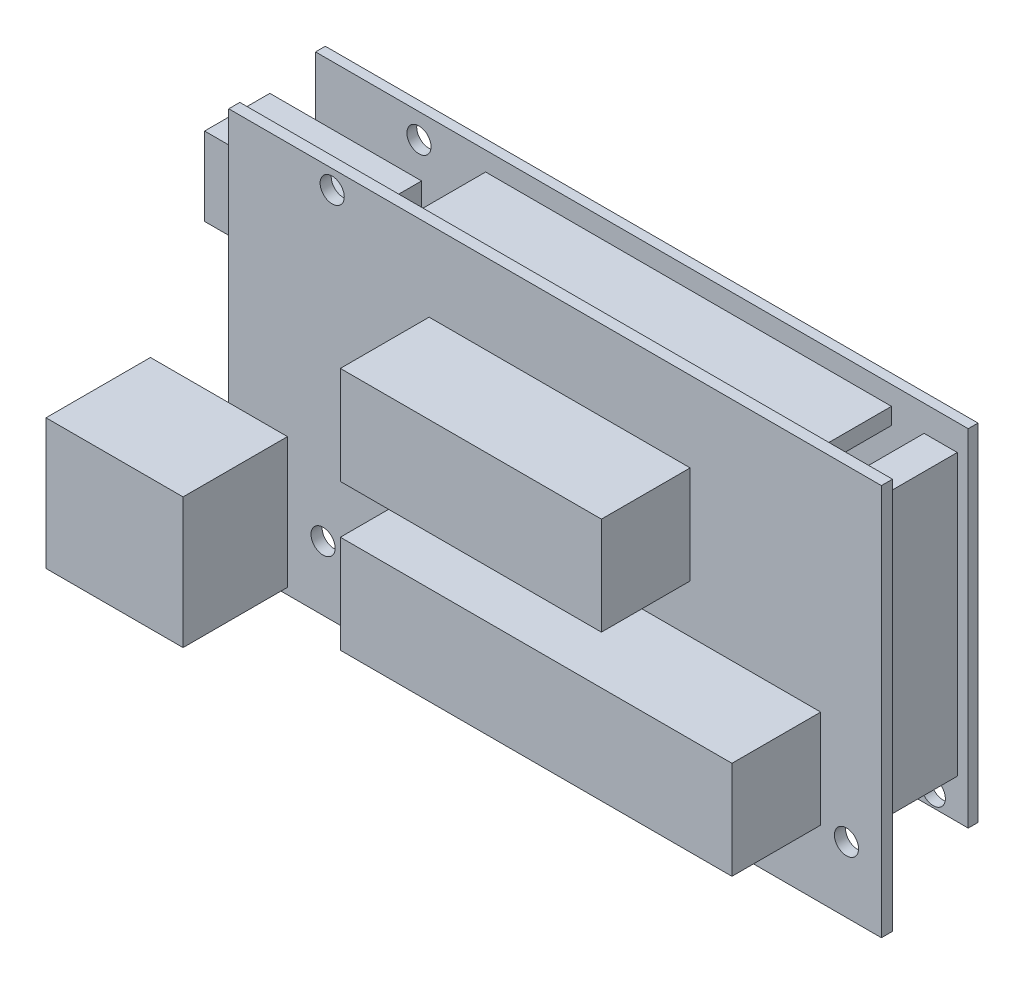
SolidWorks part; units mm, degrees
ref_plane "Plano frontal" through (0, 0, 0) normal (0, 0, 1) x (1, 0, 0)
ref_plane "Plano superior" through (0, 0, 0) normal (0, 1, 0) x (1, 0, 0)
ref_plane "Plano direito" through (0, 0, 0) normal (1, 0, 0) x (0, 0, -1)
sketch "Esboço1" plane through (0, 0, 0) normal (0, 0, 1) x (1, 0, 0)
  line L1 (-50, 30) -> (50, 30)
  line L2 (-50, 30) -> (-50, -30)
  line L3 (-50, -30) -> (50, -30)
  line L4 (50, 30) -> (50, -30)
  line L5 (-50, 30) -> (50, -30) construction
  line L6 (-50, -30) -> (50, 30) construction
  circle A0 centre (-34.15, 27.15) radius 1.85
  circle A1 centre (-35.55, -20.15) radius 1.85
  circle A2 centre (44.65, -19.95) radius 1.85
  point P0 (0, 0)
  dimension "D3" = 1
  dimension "D4" = 3.7
  dimension "D5" = 14
  dimension "D6" = 12.6
  dimension "D7" = 8
  dimension "D8" = 3.5
  dimension "D9" = 8.2
  dimension "D1" = 60
  dimension "D2" = 100
extrude "Ressalto-extrusão1" add sketch "Esboço1" along normal blind 1.7
sketch "Esboço2" plane through (0, 0, 1.7) normal (0, 0, 1) x (1, 0, 0)
  line L0 (-50, -30) -> (50, -30) construction
  line L1 (-19.3, -4.7) -> (40.7, -4.7)
  line L2 (-19.3, -4.7) -> (-19.3, -19.7)
  line L3 (-19.3, -19.7) -> (40.7, -19.7)
  line L4 (40.7, -4.7) -> (40.7, -19.7)
  line L5 (50, -30) -> (50, 30) construction
  line L7 (-19.3, 2.7) -> (20.7, 2.7)
  line L8 (-19.3, 2.7) -> (-19.3, 17.7)
  line L9 (-19.3, 17.7) -> (20.7, 17.7)
  line L10 (20.7, 2.7) -> (20.7, 17.7)
  dimension "D1" = 60
  dimension "D2" = 15
  dimension "D3" = 10.3
  dimension "D4" = 9.3
  dimension "D5" = 40
  dimension "D6" = 7.4
extrude "Ressalto-extrusão2" add sketch "Esboço2" along normal blind 13.6
sketch "Esboço3" plane through (0, 0, 0) normal (0, 0, -1) x (-1, 0, 0)
  line L0 (50, -30) -> (-50, -30) construction
  line L1 (50, 30.9) -> (-50, 30.9)
  line L2 (50, 30.9) -> (50, -22.1)
  line L3 (50, -22.1) -> (-50, -22.1)
  line L4 (-50, 30.9) -> (-50, -22.1)
  line L5 (50, 30) -> (50, -30) construction
  line L6 (-50, -30) -> (-50, 30) construction
  circle A0 centre (-44.65, -19.95) radius 1.85 construction
  circle A1 centre (34.15, 27.15) radius 1.85 construction
  circle A2 centre (35.55, -20.15) radius 1.85 construction
  circle A3 centre (-44.65, -19.95) radius 1.85
  circle A4 centre (34.15, 27.15) radius 1.85
  circle A5 centre (35.55, -20.15) radius 1.85
  dimension "D1" = 7.9
  dimension "D2" = 53
extrude "Ressalto-extrusão6" add sketch "Esboço3" along normal blind 1.5 from offset 11.6 separate body
sketch "Esboço4" plane through (0, 0, -11.6) normal (0, 0, 1) x (1, 0, 0)
  line L1 (-23.9415, 27.9898) -> (38.2426, 27.9898)
  line L2 (-23.9415, 27.9898) -> (-23.9415, 25.4498)
  line L3 (-23.9415, 25.4498) -> (38.2426, 25.4498)
  line L4 (38.2426, 27.9898) -> (38.2426, 25.4498)
  line L5 (48.3249, 26.9052) -> (43.2449, 26.9052)
  line L6 (48.3249, 26.9052) -> (48.3249, -16.0526)
  line L7 (48.3249, -16.0526) -> (43.2449, -16.0526)
  line L8 (43.2449, 26.9052) -> (43.2449, -16.0526)
  line L9 (38.2426, -19.9599) -> (-17.8292, -19.9599)
  line L10 (38.2426, -19.9599) -> (38.2426, -17.4199)
  line L11 (38.2426, -17.4199) -> (-17.8292, -17.4199)
  line L12 (-17.8292, -19.9599) -> (-17.8292, -17.4199)
  dimension "D1" = 2.54
  dimension "D2" = 5.08
extrude "Ressalto-extrusão8" add sketch "Esboço4" along normal up to surface (11.6 mm away) up to face at (0, 0, 0)
sketch "Esboço6" plane through (0, 0, 1.7) normal (0, 0, 1) x (1, 0, 0)
  line L0 (-50, -30) -> (50, -30) construction
  line L1 (-62, -9) -> (-41, -9)
  line L2 (-62, -9) -> (-62, -29)
  line L3 (-62, -29) -> (-41, -29)
  line L4 (-41, -9) -> (-41, -29)
  line L5 (-50, 30) -> (-50, -30) construction
  point P4 (-36.931, -25.6688)
  point P5 (-60.8994, -24.8784)
  dimension "D1" = 20
  dimension "D2" = 1
  dimension "D3" = 12
  dimension "D4" = 21
extrude "Ressalto-extrusão9" add sketch "Esboço6" along normal blind 16
sketch "Esboço7" plane through (0, 0, -11.6) normal (0, 0, 1) x (1, 0, 0)
  line L0 (-50, 30.9) -> (50, 30.9) construction
  line L1 (-33.753, 21.9) -> (-57, 21.9)
  line L2 (-33.753, 21.9) -> (-33.753, 9.9)
  line L3 (-33.753, 9.9) -> (-57, 9.9)
  line L4 (-57, 21.9) -> (-57, 9.9)
  line L5 (-50, -22.1) -> (-50, 30.9) construction
  dimension "D1" = 9
  dimension "D2" = 12
  dimension "D3" = 7
extrude "Ressalto-extrusão10" add sketch "Esboço7" along normal blind 10
equation "\"D5@Esboço2\"=\"D1@Esboço2\"*2/3"
equation "\"D2@Esboço4\"=\"D1@Esboço4\"*2"
